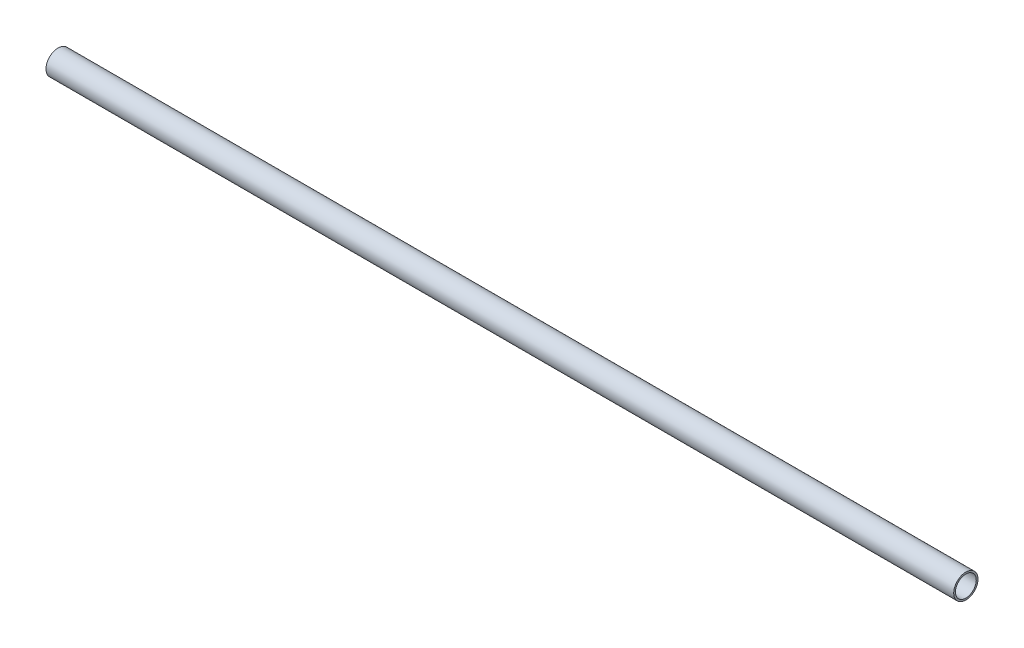
SolidWorks part; units mm, degrees
material "Thornel Mat VMA"
ref_plane "Ön Düzlem" through (0, 0, 0) normal (0, 0, 1) x (1, 0, 0)
ref_plane "Üst Düzlem" through (0, 0, 0) normal (0, 1, 0) x (1, 0, 0)
ref_plane "Sağ Düzlem" through (0, 0, 0) normal (1, 0, 0) x (0, 0, -1)
sketch "Çizim1" plane through (0, 0, 0) normal (1, 0, 0) x (0, 0, -1)
  circle A0 centre (0, 0) radius 7
  circle A1 centre (0, 0) radius 6
  dimension "D1" = 14
  dimension "D2" = 12
extrude "Yükseklik-Ekstrüzyon1" add sketch "Çizim1" along normal mid plane 523
sketch "Çizim2" plane through (261.5, 0, 0) normal (1, 0, 0) x (0, 0, -1)
  line L0 (0, -7) -> (0, 7) construction
  circle A0 centre (0, 0) radius 7 construction
  point P7 (0, 0)
